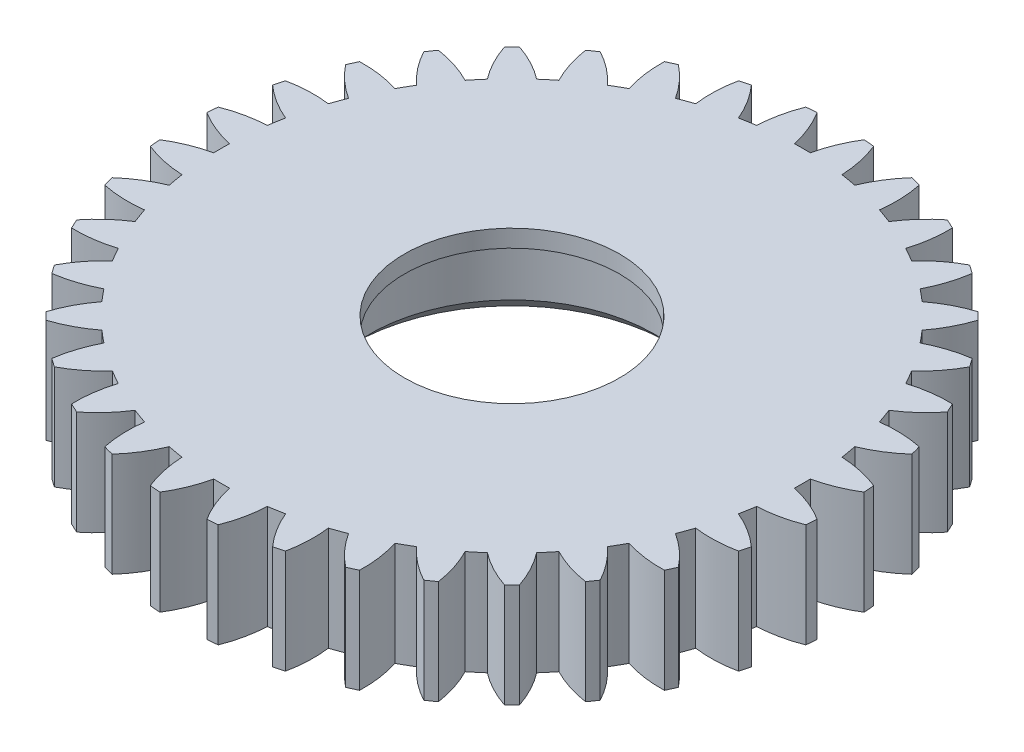
SolidWorks part; units mm, degrees
material "PLA"
ref_plane "Front Plane" through (0, 0, 0) normal (0, 0, 1) x (1, 0, 0)
ref_plane "Top Plane" through (0, 0, 0) normal (0, 1, 0) x (1, 0, 0)
ref_plane "Right Plane" through (0, 0, 0) normal (1, 0, 0) x (0, 0, -1)
sketch "Sketch1" plane through (0, 0, 0) normal (0, 1, 0) x (1, 0, 0)
  circle A0 centre (0, 0) radius 18 construction
  circle A1 centre (0, 0) radius 19
  dimension "D1" = 36
  dimension "D2" = 38
extrude "Boss-Extrude1" add sketch "Sketch1" along normal blind 6 contours A1
sketch "Sketch2" plane through (0, 6, 0) normal (0, 1, 0) x (1, 0, 0)
  line L0 (0, -1000) -> (0, 49000) construction
  arc B0 (0.4547, 16.7428) -> (-0.4547, 16.7428) centre (0, 0) ccw
  arc B1 (1.3689, 18.9761) -> (-1.3689, 18.9761) centre (0, 0) ccw
  arc B2 (-0.4547, 16.7428) -> (-1.3689, 18.9761) centre (-7.4808, 15.1702) ccw
  arc B3 (1.3689, 18.9761) -> (0.4547, 16.7428) centre (7.4808, 15.1702) ccw
  dimension "D1" = 16.749
sketch_block_instance "Block2-1"
sketch_block "Block2"
extrude "Cut-Extrude1" cut sketch "Sketch2" against normal up to surface (6 mm away) up to face at (0, 0, 19)
pattern_circular "CirPattern1" count 36 over 360 about axis through (0, 0, 0) along (0, 1, 0) of "Cut-Extrude1"
sketch "Sketch3" plane through (0, 6, 0) normal (0, 1, 0) x (1, 0, 0)
  circle A0 centre (0, 0) radius 8.2
  dimension "D1" = 16.4
extrude "Cut-Extrude2" cut sketch "Sketch3" against normal through all
sketch "Sketch4" plane through (0, 6, 0) normal (0, 1, 0) x (1, 0, 0)
  circle A0 centre (0, 0) radius 8.2
  circle A1 centre (0, 0) radius 6.2
  circle A2 centre (0, 0) radius 8.2 construction
  dimension "D1" = 2
extrude "Boss-Extrude2" add sketch "Sketch4" against normal blind 1
chamfer "Chamfer1" distance 1 angle 45 1 edges at (0, 0, 8.2)
